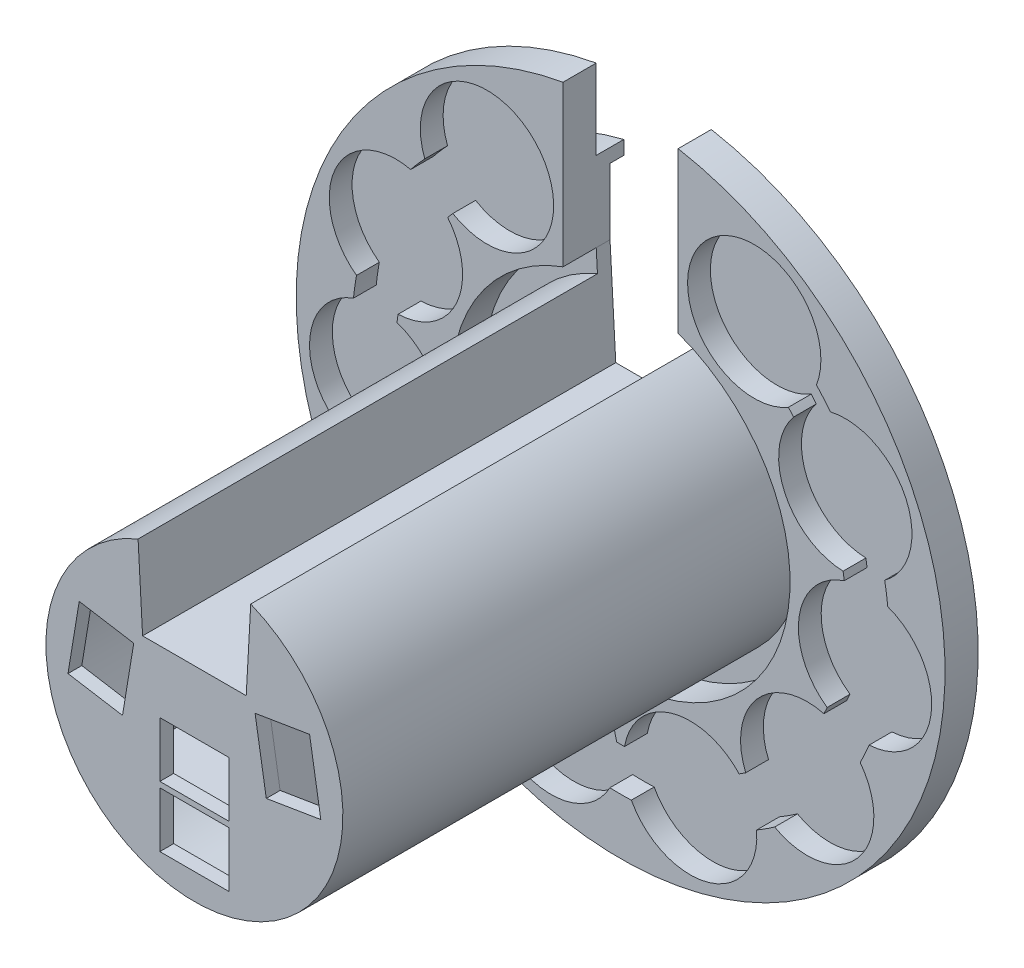
SolidWorks part; units mm, degrees
material "PBT General Purpose"
ref_plane "Front Plane" through (0, 0, 0) normal (0, 0, 1) x (1, 0, 0)
ref_plane "Top Plane" through (0, 0, 0) normal (0, 1, 0) x (1, 0, 0)
ref_plane "Right Plane" through (0, 0, 0) normal (1, 0, 0) x (0, 0, -1)
sketch "Basic_Shape_Sketch" plane through (0, 0, 0) normal (0, 0, 1) x (1, 0, 0)
  circle A0 centre (0, 0) radius 24.5318
  circle A1 centre (0, 0) radius 46.9683
  dimension "D1" = 49.0635
  dimension "D2" = 93.9365
extrude "Basic_Shape" add sketch "Basic_Shape_Sketch" along normal blind 4.8
sketch "Battery_Slot_Sketch" plane through (0, 0, 4.8) normal (0, 0, 1) x (1, 0, 0)
  line L0 (0, 0) -> (0, -46.9682) construction
  line L1 (0, 0) -> (-6.9099, -23.5385) construction
  line L2 (-6.9099, -23.5385) -> (-10.0698, -34.3025) construction
  line L3 (-10.0698, -34.3025) -> (-13.2296, -45.0665) construction
  circle A0 centre (0, 0) radius 46.9682 construction
  circle A1 centre (-10.0698, -34.3025) radius 9.65
  circle A2 centre (0, 0) radius 24.5318 construction
  dimension "D1" = 19.3
  dimension "D2" = 16.36
extrude "Battery_Slot" cut sketch "Battery_Slot_Sketch" against normal blind 3.3
pattern_circular "Battery_Slot_Pattern" count 5 every 32.72 about axis through (0, 0, 0) along (0, 0, 1) of "Battery_Slot"
mirror "Battery_Slot_Mirror" about plane through (0, 0, 0) normal (1, 0, 0) of "Battery_Slot_Pattern", "Battery_Slot"
sketch "Slit_Sketch" plane through (0, 0, 4.8) normal (0, 0, 1) x (1, 0, 0)
  line L0 (-8.33, 46.2237) -> (-8.33, 23.0742)
  line L1 (8.33, 46.2237) -> (8.33, 23.0742)
  line L2 (-8.33, 23.0742) -> (8.33, 23.0742)
  circle A0 centre (0, 0) radius 46.9682 construction
  circle A1 centre (0, 0) radius 24.5318 construction
  arc A2 (8.33, 46.2237) -> (-8.33, 46.2237) centre (0, 46.2237) ccw
  dimension "D1" = 16.66
extrude "Slit" cut sketch "Slit_Sketch" against normal through all
sketch "Bus_Slit_Sketch" plane through (0, 0, 4.8) normal (0, 0, 1) x (1, 0, 0)
  arc A0 (-9.7545, 31.1326) -> (9.7545, 31.1326) centre (0, 0) ccw
  circle A1 centre (-19.3451, 30.0638) radius 9.65 construction
  circle A2 centre (19.3451, 30.0638) radius 9.65 construction
  arc A3 (-12.4591, 36.8244) -> (12.4591, 36.8244) centre (0, 0) ccw
  circle A4 centre (19.3451, 30.0638) radius 9.65 construction
  arc A5 (-12.4591, 36.8244) -> (-9.7545, 31.1326) centre (-19.3451, 30.0638) cw
  arc A6 (9.7545, 31.1326) -> (12.4591, 36.8244) centre (19.3451, 30.0638) cw
  dimension "D1" = 9.65
  dimension "D2" = 9.65
  dimension "D3" = 32.625
  dimension "D4" = 38.875
extrude "Bus_Slit" cut sketch "Bus_Slit_Sketch" against normal blind 3.3
sketch "Cap_2_Sketch" plane through (0, 0, 0) normal (0, 0, -1) x (-1, 0, 0)
  line L0 (-8.33, 23.0742) -> (-8.33, 46.2237) construction
  line L1 (8.33, 46.2237) -> (8.33, 23.0742) construction
  line L2 (-8.33, 34.6489) -> (-8.33, 23.0742)
  line L3 (-8.33, 23.0742) -> (8.33, 23.0742)
  line L4 (8.33, 23.0742) -> (8.33, 34.6489)
  arc A0 (-8.33, 34.6489) -> (8.33, 34.6489) centre (0, 0) ccw
extrude "Cap_2" add sketch "Cap_2_Sketch" along normal blind 2
sketch "Sketch1" plane through (0, 0, 0) normal (0, 0, 1) x (1, 0, 0)
  line L5 (-7.5, 8.0742) -> (-8.33, 23.0742) construction
  line L6 (-7.5, 8.0742) -> (7.5, 8.0742)
  line L7 (-8.33, 23.0742) -> (8.33, 23.0742) construction
  line L8 (7.5, 8.0742) -> (8.154, 19.8938)
  line L9 (-7.5, 8.0742) -> (-8.154, 19.8938)
  arc A1 (8.154, 19.8938) -> (-8.154, 19.8938) centre (0, 0) cw
  point P7 (0, 8.0742)
  dimension "D3" = 21.5
  dimension "D1" = 15
  dimension "D2" = 15
extrude "Plunger" add sketch "Sketch1" along normal blind 66.5
sketch "Sketch11" plane through (0, 0, -2) normal (0, 0, -1) x (-1, 0, 0)
  line L0 (-8.6137, 19.1521) -> (-7.9731, 7.5742)
  line L1 (-7.9731, 7.5742) -> (7.9731, 7.5742)
  line L2 (7.9731, 7.5742) -> (8.6137, 19.1521)
  line L3 (7.5, 8.0742) -> (-7.5, 8.0742) construction
  line L4 (-7.5, 8.0742) -> (-8.154, 19.8938) construction
  line L5 (7.5, 8.0742) -> (8.154, 19.8938) construction
  arc A0 (8.6137, 19.1521) -> (-8.6137, 19.1521) centre (0, 0) cw
  arc A1 (-8.154, 19.8938) -> (8.154, 19.8938) centre (0, 0) ccw construction
  point P14 (0, 7.5742)
  point P24 (8.2934, 13.3631)
  dimension "D1" = 0.5
  dimension "D2" = 0.5
  dimension "D3" = 0.5
extrude "Plunger Cavity" cut sketch "Sketch11" against normal blind 66.5
sketch "Sketch10" plane through (0, 0, -2) normal (0, 0, -1) x (-1, 0, 0)
  line L0 (8.33, 34.6489) -> (8.33, 23.0742) construction
  line L1 (-8.33, 23.0742) -> (-8.33, 34.6489) construction
  line L2 (-8.33, 34.6489) -> (-8.33, 32.6489)
  line L3 (8.33, 34.6489) -> (8.33, 32.6489)
  arc A0 (-8.33, 34.6489) -> (8.33, 34.6489) centre (0, 0) ccw
  arc A1 (-8.33, 32.6489) -> (8.33, 32.6489) centre (0, 0) ccw
  dimension "D1" = 2
extrude "Lip" add sketch "Sketch10" along normal blind 2
sketch "Sketch12" plane through (0, 0, 0) normal (0, 0, 1) x (1, 0, 0)
  line L0 (-7.5, 8.0742) -> (-8.33, 23.0742)
  line L1 (-8.33, 23.0742) -> (8.33, 23.0742)
  line L2 (8.33, 23.0742) -> (7.5, 8.0742)
  line L3 (7.5, 8.0742) -> (-7.5, 8.0742)
extrude "Extra_Cut" cut sketch "Sketch12" against normal through all
sketch "Sketch13" plane through (0, 0, -2) normal (0, 0, -1) x (-1, 0, 0)
  line L16 (-9, -9.7237) -> (9, -9.7237)
  line L17 (-9, -9.7237) -> (-9, -18.9737)
  line L18 (-17.2599, 11.9622) -> (-8.1328, 10.4598)
  line L23 (-8.1328, 10.4598) -> (-11.0563, -7.3012)
  line L24 (-11.0563, -7.3012) -> (-20.1835, -5.7988)
  line L25 (-20.1835, -5.7988) -> (-17.2599, 11.9622)
  line L26 (17.2599, 11.9622) -> (20.1835, -5.7988)
  line L27 (20.1835, -5.7988) -> (11.0563, -7.3012)
  line L28 (11.0563, -7.3012) -> (8.1328, 10.4598)
  line L29 (8.1328, 10.4598) -> (17.2599, 11.9622)
  line L30 (-7.9731, 7.5742) -> (-8.6137, 19.1521) construction
  line L31 (0, -8.923) -> (0, -9.7237) construction
  line L32 (8.6137, 19.1521) -> (7.9731, 7.5742) construction
  line L33 (-9, -8.923) -> (-9, 0.327)
  line L38 (-9, -8.923) -> (9, -8.923)
  line L39 (-9, 0.327) -> (9, 0.327)
  line L40 (9, -8.923) -> (9, 0.327)
  line L41 (9, -9.7237) -> (9, -18.9737)
  line L42 (-9, -18.9737) -> (9, -18.9737)
  line L45 (0, 0.327) -> (0, 7.5742) construction
  line L46 (7.9731, 7.5742) -> (-7.9731, 7.5742) construction
  line L47 (0, -9.7237) -> (0, -18.9737) construction
  line L49 (9, 0.327) -> (9.8007, 0.327) construction
  line L50 (-9, 0.327) -> (-9.8007, 0.327) construction
  arc A0 (-8.6137, 19.1521) -> (8.6137, 19.1521) centre (0, 0) ccw construction
  arc A2 (-8.6137, 19.1521) -> (8.6137, 19.1521) centre (0, 0) ccw construction
  dimension "D1" = 18
  dimension "D2" = 9.25
  dimension "D3" = 9.25
  dimension "D4" = 18
  dimension "D5" = 9.25
  dimension "D6" = 18
  dimension "D7" = 18
  dimension "D8" = 9.25
ref_plane "Plane1" through (0, 0, 13) normal (0, 0, -1) x (-1, 0, 0)
sketch "Sketch14" plane through (0, 0, 13) normal (0, 0, -1) x (-1, 0, 0)
  line L0 (-8.0945, 9.7686) -> (-12.4823, -16.8876)
  line L1 (-7.9731, 7.5742) -> (-8.6137, 19.1521) construction
  line L2 (-7.9591, 7.5742) -> (-10.6993, -9.073)
  line L3 (7.9731, 7.5742) -> (-7.9731, 7.5742) construction
  line L4 (-8.1328, 10.4598) -> (-11.0563, -7.3012) construction
  line L6 (-7.9591, 7.5742) -> (-8.0945, 9.7686)
  line L7 (7.9591, 7.5742) -> (10.6993, -9.073)
  line L8 (7.9731, 7.5742) -> (-7.9731, 7.5742) construction
  line L10 (7.9591, 7.5742) -> (8.0945, 9.7686)
  line L11 (8.6137, 19.1521) -> (7.9731, 7.5742) construction
  line L12 (8.0945, 9.7686) -> (12.4823, -16.8876)
  line L13 (11.0563, -7.3012) -> (8.1328, 10.4598) construction
  line L14 (-10.6993, -9.073) -> (10.6993, -9.073)
  line L16 (-9, -8.923) -> (9, -8.923) construction
  line L17 (-12.0292, -17.2133) -> (-10.7717, -9.5737)
  line L18 (-10.7717, -9.5737) -> (10.7717, -9.5737)
  line L19 (10.7717, -9.5737) -> (12.0292, -17.2133)
  line L20 (-9, -9.7237) -> (9, -9.7237) construction
  arc A1 (-8.6137, 19.1521) -> (8.6137, 19.1521) centre (0, 0) ccw construction
  arc A2 (-8.6137, 19.1521) -> (8.6137, 19.1521) centre (0, 0) ccw construction
  arc A3 (-12.0292, -17.2133) -> (-12.4823, -16.8876) centre (0, 0) cw
  arc A4 (12.4823, -16.8876) -> (12.0292, -17.2133) centre (0, 0) cw
  dimension "D1" = 0.15
  dimension "D2" = 0.15
  dimension "D3" = 0.15
  dimension "D4" = 0.15
  dimension "D5" = 0.15
  dimension "D6" = 0.15
  dimension "D7" = 0.5
  dimension "D8" = 0.5
extrude "Barriers" add sketch "Sketch14" against normal blind 51.5
sketch "Sketch15" plane through (0, 0, 64.5) normal (0, 0, -1) x (-1, 0, 0)
  line L0 (-16.6762, 7.8123) -> (-8.7825, 6.5129)
  line L1 (-16.6762, 7.8123) -> (-18.3004, -2.0549)
  line L2 (-8.7825, 6.5129) -> (-10.4067, -3.3543)
  line L3 (-18.3004, -2.0549) -> (-10.4067, -3.3543)
  line L4 (-8.1328, 10.4598) -> (-11.0563, -7.3012) construction
  line L5 (-12.7293, 7.1626) -> (-12.0797, 11.1095) construction
  line L6 (-17.2599, 11.9622) -> (-8.1328, 10.4598) construction
  line L7 (-14.3535, -2.7046) -> (-15.0032, -6.6515) construction
  line L8 (-11.0563, -7.3012) -> (-20.1835, -5.7988) construction
  line L9 (8.7825, 6.5129) -> (16.6762, 7.8123)
  line L10 (8.7825, 6.5129) -> (10.4067, -3.3543)
  line L11 (16.6762, 7.8123) -> (18.3004, -2.0549)
  line L12 (10.4067, -3.3543) -> (18.3004, -2.0549)
  line L13 (8.1328, 10.4598) -> (17.2599, 11.9622) construction
  line L14 (11.0563, -7.3012) -> (8.1328, 10.4598) construction
  line L15 (12.7293, 7.1626) -> (12.0797, 11.1095) construction
  line L16 (14.3535, -2.7046) -> (15.0032, -6.6515) construction
  line L17 (20.1835, -5.7988) -> (11.0563, -7.3012) construction
  line L18 (-9, -8.923) -> (9, -8.923) construction
  line L19 (-5, -8.923) -> (5, -8.923)
  line L20 (-5, -8.923) -> (-5, -0.923)
  line L21 (-5, -0.923) -> (5, -0.923)
  line L22 (5, -8.923) -> (5, -0.923)
  line L23 (-9, -9.7237) -> (9, -9.7237) construction
  line L24 (-5, -9.7237) -> (5, -9.7237)
  line L25 (-5, -9.7237) -> (-5, -17.7237)
  line L26 (-5, -17.7237) -> (5, -17.7237)
  line L27 (5, -9.7237) -> (5, -17.7237)
  point P35 (0, -0.923)
  point P42 (0, -17.7237)
  dimension "D1" = 10
  dimension "D2" = 8
  dimension "D3" = 8
  dimension "D4" = 10
  dimension "D5" = 8
  dimension "D6" = 10
extrude "Cut-Extrude6" cut sketch "Sketch15" against normal through all
